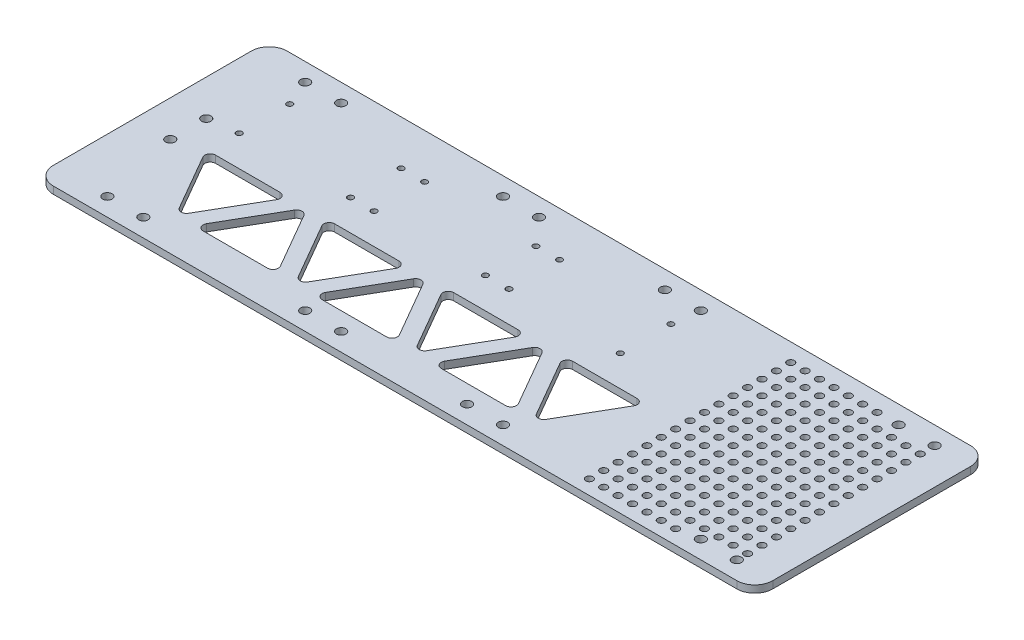
SolidWorks part; units mm, degrees
ref_plane "前视基准面" through (0, 0, 0) normal (0, 0, 1) x (1, 0, 0)
ref_plane "上视基准面" through (0, 0, 0) normal (0, 1, 0) x (1, 0, 0)
ref_plane "右视基准面" through (0, 0, 0) normal (1, 0, 0) x (0, 0, -1)
other "Configuration Table"
sketch "草图1" plane through (0, 0, 0) normal (0, 1, 0) x (1, 0, 0)
  line L1 (0, 0) -> (400, 0)
  line L2 (0, 0) -> (0, -130)
  line L3 (0, -130) -> (400, -130)
  line L4 (400, 0) -> (400, -130)
  dimension "D1" = 130
  dimension "D2" = 400
extrude "凸台-拉伸1" add sketch "草图1" along normal blind 4
sketch "草图2" plane through (0, 4, 0) normal (0, 1, 0) x (1, 0, 0)
  line L0 (45, -59.5) -> (64, -59.5) construction
  line L1 (41, -59.5) -> (45, -59.5)
  line L2 (41, -59.5) -> (41, -75.5)
  line L3 (41, -75.5) -> (45, -75.5)
  line L4 (45, -59.5) -> (45, -75.5)
  line L5 (64, -59.5) -> (68, -59.5)
  line L6 (64, -59.5) -> (64, -75.5)
  line L7 (64, -75.5) -> (68, -75.5)
  line L8 (68, -59.5) -> (68, -75.5)
  line L9 (36.21, -24.8) -> (98.11, -24.8) construction
  line L10 (36.21, -24.8) -> (36.21, -52.9) construction
  line L11 (36.21, -52.9) -> (98.11, -52.9) construction
  line L12 (98.11, -24.8) -> (98.11, -52.9) construction
  line L13 (54.5, -59.5) -> (54.5, -65.549) construction
  line L14 (0, -65) -> (40, -65) construction
  line L15 (0, 0) -> (0, -130) construction
  line L16 (116, -59.5) -> (120, -59.5)
  line L17 (116, -59.5) -> (116, -75.5)
  line L18 (116, -75.5) -> (120, -75.5)
  line L19 (120, -59.5) -> (120, -75.5)
  line L20 (139, -59.5) -> (143, -59.5)
  line L21 (139, -59.5) -> (139, -75.5)
  line L22 (139, -75.5) -> (143, -75.5)
  line L23 (143, -59.5) -> (143, -75.5)
  line L24 (120, -59.5) -> (139, -59.5) construction
  line L25 (111.21, -24.8) -> (173.11, -24.8) construction
  line L26 (111.21, -24.8) -> (111.21, -52.9) construction
  line L27 (111.21, -52.9) -> (173.11, -52.9) construction
  line L28 (173.11, -24.8) -> (173.11, -52.9) construction
  line L29 (129.5, -59.5) -> (129.5, -65.549) construction
  line L30 (191, -59.5) -> (195, -59.5)
  line L31 (191, -59.5) -> (191, -75.5)
  line L32 (191, -75.5) -> (195, -75.5)
  line L33 (195, -59.5) -> (195, -75.5)
  line L34 (214, -59.5) -> (218, -59.5)
  line L35 (214, -59.5) -> (214, -75.5)
  line L36 (214, -75.5) -> (218, -75.5)
  line L37 (218, -59.5) -> (218, -75.5)
  line L38 (195, -59.5) -> (214, -59.5) construction
  line L39 (186.21, -24.8) -> (248.11, -24.8) construction
  line L40 (186.21, -24.8) -> (186.21, -52.9) construction
  line L41 (186.21, -52.9) -> (248.11, -52.9) construction
  line L42 (248.11, -24.8) -> (248.11, -52.9) construction
  line L43 (204.5, -59.5) -> (204.5, -65.549) construction
  circle A0 centre (36.21, -52.9) radius 1.6
  circle A1 centre (36.21, -24.8) radius 1.6
  circle A2 centre (98.11, -52.9) radius 1.6
  circle A3 centre (98.11, -24.8) radius 1.6
  circle A4 centre (40, -65) radius 1 construction
  circle A5 centre (111.21, -52.9) radius 1.6
  circle A6 centre (111.21, -24.8) radius 1.6
  circle A7 centre (173.11, -52.9) radius 1.6
  circle A8 centre (173.11, -24.8) radius 1.6
  circle A9 centre (115, -65) radius 1 construction
  circle A10 centre (186.21, -52.9) radius 1.6
  circle A11 centre (186.21, -24.8) radius 1.6
  circle A12 centre (248.11, -52.9) radius 1.6
  circle A13 centre (248.11, -24.8) radius 1.6
  circle A14 centre (190, -65) radius 1 construction
  dimension "D9" = 2
  dimension "D13" = 3.2
  dimension "D1" = 4
  dimension "D2" = 4
  dimension "D3" = 19
  dimension "D4" = 16
  dimension "D5" = 28.1
  dimension "D6" = 61.9
  dimension "D7" = 12.1
  dimension "D8" = 3.79
  dimension "D10" = 14.5
  dimension "D11" = 5.5
  dimension "D12" = 40
  dimension "D14" = 3
extrude "切除-拉伸1" cut sketch "草图2" against normal blind 4 contours A1 | A0 | A3 | A2 | A5 | A7 | A8 | A11 | A10 | A13 | A12 | A6
sketch "草图3" plane through (0, 4, 0) normal (0, 1, 0) x (1, 0, 0)
  line L0 (0, -65) -> (25.2073, -65) construction
  line L1 (0, 0) -> (0, -130) construction
  line L2 (20, -75) -> (20, -55) construction
  circle A0 centre (20, -75) radius 2.6
  circle A1 centre (20, -55) radius 2.6
  dimension "D1" = 5.2
  dimension "D2" = 20
  dimension "D3" = 20
extrude "切除-拉伸2" cut sketch "草图3" against normal through all
sketch "草图4" plane through (0, 4, 0) normal (0, 1, 0) x (1, 0, 0)
  line L0 (67.16, -24.8) -> (67.16, 18.7842) construction
  line L1 (0, -130) -> (300, -130)
  line L2 (0, -130) -> (0, -180)
  line L3 (0, -180) -> (300, -180)
  line L4 (300, -130) -> (300, -180)
  line L5 (36.21, -24.8) -> (98.11, -24.8) construction
  line L6 (142.16, -24.8) -> (142.16, 18.7842) construction
  line L7 (111.21, -24.8) -> (173.11, -24.8) construction
  line L8 (217.16, -24.8) -> (217.16, 18.7842) construction
  line L9 (186.21, -24.8) -> (248.11, -24.8) construction
  line L10 (42.16, 30) -> (42.16, 0)
  line L11 (42.16, 30) -> (92.16, 30)
  line L12 (42.16, 0) -> (92.16, 0)
  line L13 (92.16, 30) -> (92.16, 0)
  line L14 (42.16, 30) -> (92.16, 0) construction
  line L15 (42.16, 0) -> (92.16, 30) construction
  line L16 (117.16, 30) -> (117.16, 0)
  line L17 (117.16, 30) -> (167.16, 30)
  line L18 (167.16, 30) -> (167.16, 0)
  line L19 (117.16, 0) -> (167.16, 0)
  line L20 (192.16, 30) -> (192.16, 0)
  line L21 (192.16, 30) -> (242.16, 30)
  line L22 (242.16, 30) -> (242.16, 0)
  line L23 (192.16, 0) -> (242.16, 0)
  point P18 (67.16, 15)
  dimension "D1" = 300
  dimension "D2" = 50
  dimension "D3" = 50
  dimension "D4" = 30
  dimension "D5" = 3
extrude "凸台-拉伸2" [suppressed] add sketch "草图4" against normal up to surface (4 mm away)
sketch "草图5" plane through (0, 4, 0) normal (0, 1, 0) x (1, 0, 0)
  line L0 (140, -10) -> (160, -10) construction
  line L1 (30, -10) -> (50, -10) construction
  line L2 (0, 0) -> (0, -130) construction
  line L3 (0, -65) -> (40, -65) construction
  line L4 (0, -65) -> (40, -65) construction
  line L5 (230, -10) -> (250, -10) construction
  line L6 (360, -10) -> (380, -10) construction
  line L7 (360, -120) -> (380, -120) construction
  line L8 (230, -120) -> (250, -120) construction
  line L9 (30, -120) -> (50, -120) construction
  line L10 (140, -120) -> (160, -120) construction
  circle A0 centre (30, -10) radius 2.6
  circle A1 centre (50, -10) radius 2.6
  circle A4 centre (140, -10) radius 2.6
  circle A5 centre (160, -10) radius 2.6
  circle A8 centre (230, -10) radius 2.6
  circle A9 centre (250, -10) radius 2.6
  circle A12 centre (360, -10) radius 2.6
  circle A13 centre (380, -10) radius 2.6
  circle A16 centre (380, -120) radius 2.6
  circle A17 centre (360, -120) radius 2.6
  circle A18 centre (250, -120) radius 2.6
  circle A19 centre (230, -120) radius 2.6
  circle A20 centre (160, -120) radius 2.6
  circle A21 centre (140, -120) radius 2.6
  circle A22 centre (50, -120) radius 2.6
  circle A23 centre (30, -120) radius 2.6
  dimension "D1" = 5.2
  dimension "D6" = 110
  dimension "D7" = 130
  dimension "D5" = 90
  dimension "D2" = 55
  dimension "D3" = 20
  dimension "D4" = 30
extrude "切除-拉伸3" cut sketch "草图5" against normal through all
sketch "草图6" plane through (0, 4, 0) normal (0, 1, 0) x (1, 0, 0)
  line L8 (390, -112) -> (346, -112)
  line L9 (346, -112) -> (346, -101)
  line L12 (346, -101) -> (332, -101)
  line L13 (332, -101) -> (332, -79)
  line L16 (332, -79) -> (346, -79)
  line L17 (346, -79) -> (346, -68)
  line L18 (346, -68) -> (390, -68)
  line L19 (390, -68) -> (390, -112)
  line L20 (0, -130) -> (400, -130) construction
  line L21 (400, -130) -> (400, 0) construction
  circle A6 centre (335.5, -114.5) radius 2.1
  circle A7 centre (335.5, -65.5) radius 2.1
  dimension "D3" = 22
  dimension "D11" = 4.2
  dimension "D1" = 44
  dimension "D2" = 44
  dimension "D4" = 11
  dimension "D5" = 14
  dimension "D6" = 14
  dimension "D7" = 13.5
  dimension "D8" = 13.5
  dimension "D9" = 54.5
  dimension "D10" = 54.5
  dimension "D12" = 18
  dimension "D13" = 10
extrude "切除-拉伸4" [suppressed] cut sketch "草图6" against normal through all
sketch "草图7" plane through (0, 4, 0) normal (0, 1, 0) x (1, 0, 0)
  line L0 (380, -66) -> (380, -110)
  line L1 (336, -66) -> (347, -66)
  line L2 (336, -66) -> (336, -110)
  line L3 (336, -110) -> (380, -110)
  line L4 (369, -52) -> (347, -52)
  line L5 (347, -52) -> (347, -66)
  line L6 (369, -66) -> (380, -66)
  line L7 (369, -52) -> (369, -66)
  line L8 (333.5, -55.5) -> (382.5, -55.5) construction
  line L9 (400, -130) -> (400, 0) construction
  line L12 (358, -110) -> (358, -52) construction
  line L13 (0, -130) -> (400, -130) construction
  circle A0 centre (333.5, -55.5) radius 2.1
  circle A1 centre (382.5, -55.5) radius 2.1
  point P10 (358, -52)
  point P13 (380, -88)
  dimension "D3" = 4.2
  dimension "D11" = 20
  dimension "D1" = 44
  dimension "D2" = 14
  dimension "D4" = 22
  dimension "D5" = 11
  dimension "D6" = 44
  dimension "D7" = 13.5
  dimension "D8" = 13.5
  dimension "D9" = 11
  dimension "D10" = 44
  dimension "D12" = 20
  dimension "D13" = 54.5
extrude "切除-拉伸5" [suppressed] cut sketch "草图7" against normal through all
sketch "草图8" plane through (0, 4, 0) normal (0, 1, 0) x (1, 0, 0)
  line L0 (400, 0) -> (0, 0) construction
  line L1 (0, 0) -> (0, -130) construction
  circle A0 centre (300, -10) radius 2
  circle A1 centre (308, -10) radius 2
  circle A2 centre (316, -10) radius 2
  circle A3 centre (324, -10) radius 2
  circle A4 centre (332, -10) radius 2
  circle A5 centre (340, -10) radius 2
  circle A6 centre (348, -10) radius 2
  circle A11 centre (308, -18) radius 2
  circle A12 centre (316, -18) radius 2
  circle A13 centre (324, -18) radius 2
  circle A14 centre (332, -18) radius 2
  circle A15 centre (340, -18) radius 2
  circle A16 centre (348, -18) radius 2
  circle A17 centre (356, -18) radius 2
  circle A18 centre (364, -18) radius 2
  circle A19 centre (372, -18) radius 2
  circle A20 centre (380, -18) radius 2
  circle A21 centre (308, -26) radius 2
  circle A22 centre (316, -26) radius 2
  circle A23 centre (324, -26) radius 2
  circle A24 centre (332, -26) radius 2
  circle A25 centre (340, -26) radius 2
  circle A26 centre (348, -26) radius 2
  circle A27 centre (356, -26) radius 2
  circle A28 centre (364, -26) radius 2
  circle A29 centre (372, -26) radius 2
  circle A30 centre (380, -26) radius 2
  circle A31 centre (308, -34) radius 2
  circle A32 centre (316, -34) radius 2
  circle A33 centre (324, -34) radius 2
  circle A34 centre (332, -34) radius 2
  circle A35 centre (340, -34) radius 2
  circle A36 centre (348, -34) radius 2
  circle A37 centre (356, -34) radius 2
  circle A38 centre (364, -34) radius 2
  circle A39 centre (372, -34) radius 2
  circle A40 centre (380, -34) radius 2
  circle A41 centre (308, -42) radius 2
  circle A42 centre (316, -42) radius 2
  circle A43 centre (324, -42) radius 2
  circle A44 centre (332, -42) radius 2
  circle A45 centre (340, -42) radius 2
  circle A46 centre (348, -42) radius 2
  circle A47 centre (356, -42) radius 2
  circle A48 centre (364, -42) radius 2
  circle A49 centre (372, -42) radius 2
  circle A50 centre (380, -42) radius 2
  circle A51 centre (308, -50) radius 2
  circle A52 centre (316, -50) radius 2
  circle A53 centre (324, -50) radius 2
  circle A54 centre (332, -50) radius 2
  circle A55 centre (340, -50) radius 2
  circle A56 centre (348, -50) radius 2
  circle A57 centre (356, -50) radius 2
  circle A58 centre (364, -50) radius 2
  circle A59 centre (372, -50) radius 2
  circle A60 centre (380, -50) radius 2
  circle A61 centre (308, -58) radius 2
  circle A62 centre (316, -58) radius 2
  circle A63 centre (324, -58) radius 2
  circle A64 centre (332, -58) radius 2
  circle A65 centre (340, -58) radius 2
  circle A66 centre (348, -58) radius 2
  circle A67 centre (356, -58) radius 2
  circle A68 centre (364, -58) radius 2
  circle A69 centre (372, -58) radius 2
  circle A70 centre (380, -58) radius 2
  circle A71 centre (308, -66) radius 2
  circle A72 centre (316, -66) radius 2
  circle A73 centre (324, -66) radius 2
  circle A74 centre (332, -66) radius 2
  circle A75 centre (340, -66) radius 2
  circle A76 centre (348, -66) radius 2
  circle A77 centre (356, -66) radius 2
  circle A78 centre (364, -66) radius 2
  circle A79 centre (372, -66) radius 2
  circle A80 centre (380, -66) radius 2
  circle A81 centre (308, -74) radius 2
  circle A82 centre (316, -74) radius 2
  circle A83 centre (324, -74) radius 2
  circle A84 centre (332, -74) radius 2
  circle A85 centre (340, -74) radius 2
  circle A86 centre (348, -74) radius 2
  circle A87 centre (356, -74) radius 2
  circle A88 centre (364, -74) radius 2
  circle A89 centre (372, -74) radius 2
  circle A90 centre (380, -74) radius 2
  circle A91 centre (308, -82) radius 2
  circle A92 centre (316, -82) radius 2
  circle A93 centre (324, -82) radius 2
  circle A94 centre (332, -82) radius 2
  circle A95 centre (340, -82) radius 2
  circle A96 centre (348, -82) radius 2
  circle A97 centre (356, -82) radius 2
  circle A98 centre (364, -82) radius 2
  circle A99 centre (372, -82) radius 2
  circle A100 centre (380, -82) radius 2
  circle A101 centre (308, -90) radius 2
  circle A102 centre (316, -90) radius 2
  circle A103 centre (324, -90) radius 2
  circle A104 centre (332, -90) radius 2
  circle A105 centre (340, -90) radius 2
  circle A106 centre (348, -90) radius 2
  circle A107 centre (356, -90) radius 2
  circle A108 centre (364, -90) radius 2
  circle A109 centre (372, -90) radius 2
  circle A110 centre (380, -90) radius 2
  circle A111 centre (308, -98) radius 2
  circle A112 centre (316, -98) radius 2
  circle A113 centre (324, -98) radius 2
  circle A114 centre (332, -98) radius 2
  circle A115 centre (340, -98) radius 2
  circle A116 centre (348, -98) radius 2
  circle A117 centre (356, -98) radius 2
  circle A118 centre (364, -98) radius 2
  circle A119 centre (372, -98) radius 2
  circle A120 centre (380, -98) radius 2
  circle A121 centre (300, -18) radius 2
  circle A122 centre (300, -26) radius 2
  circle A123 centre (300, -34) radius 2
  circle A124 centre (300, -42) radius 2
  circle A125 centre (300, -50) radius 2
  circle A126 centre (300, -58) radius 2
  circle A127 centre (300, -66) radius 2
  circle A128 centre (300, -74) radius 2
  circle A129 centre (300, -82) radius 2
  circle A130 centre (300, -90) radius 2
  circle A131 centre (300, -98) radius 2
  circle A132 centre (300, -106) radius 2
  circle A133 centre (308, -106) radius 2
  circle A134 centre (316, -106) radius 2
  circle A135 centre (324, -106) radius 2
  circle A136 centre (332, -106) radius 2
  circle A137 centre (340, -106) radius 2
  circle A138 centre (348, -106) radius 2
  circle A139 centre (356, -106) radius 2
  circle A140 centre (364, -106) radius 2
  circle A141 centre (372, -106) radius 2
  circle A142 centre (380, -106) radius 2
  circle A143 centre (300, -114) radius 2
  circle A144 centre (308, -114) radius 2
  circle A145 centre (316, -114) radius 2
  circle A146 centre (324, -114) radius 2
  circle A147 centre (332, -114) radius 2
  circle A148 centre (340, -114) radius 2
  circle A149 centre (348, -114) radius 2
  circle A150 centre (356, -114) radius 2
  circle A151 centre (364, -114) radius 2
  circle A152 centre (372, -114) radius 2
  circle A153 centre (380, -114) radius 2
  circle A154 centre (300, -122) radius 2
  circle A155 centre (308, -122) radius 2
  circle A156 centre (316, -122) radius 2
  circle A157 centre (324, -122) radius 2
  circle A158 centre (332, -122) radius 2
  circle A159 centre (340, -122) radius 2
  circle A160 centre (348, -122) radius 2
  circle A165 centre (356, -10) radius 2 [skipped]
  circle A166 centre (364, -10) radius 2 [skipped]
  circle A167 centre (372, -10) radius 2 [skipped]
  circle A168 centre (380, -10) radius 2 [skipped]
  circle A169 centre (356, -122) radius 2 [skipped]
  circle A170 centre (364, -122) radius 2 [skipped]
  circle A171 centre (372, -122) radius 2 [skipped]
  circle A172 centre (380, -122) radius 2 [skipped]
  dimension "D1" = 4
  dimension "D3" = 300
  dimension "D2" = 10
  dimension "D4" = 11
  dimension "D5" = 15
extrude "切除-拉伸6" cut sketch "草图8" against normal through all
sketch "草图9" plane through (0, 4, 0) normal (0, 1, 0) x (1, 0, 0)
  line L0 (0, -130) -> (400, -130) construction
  line L1 (185.4166, -77) -> (234.4166, -77) construction
  line L2 (185.4166, -77) -> (185.4166, -126) construction
  line L3 (185.4166, -126) -> (234.4166, -126) construction
  line L4 (234.4166, -77) -> (234.4166, -126) construction
  circle A0 centre (185.4166, -77) radius 1.6
  circle A1 centre (185.4166, -126) radius 1.6
  circle A2 centre (234.4166, -126) radius 1.6
  circle A3 centre (234.4166, -77) radius 1.6
  dimension "D3" = 3.2
  dimension "D1" = 49
  dimension "D2" = 49
  dimension "D4" = 4
extrude "切除-拉伸7" [suppressed] cut sketch "草图9" against normal through all
fillet "圆角1" radius 10 4 edges at (400, 2, 130) (400, 2, 0) (0, 2, 0) (0, 2, 130)
sketch "草图10" plane through (0, 4, 0) normal (0, 1, 0) x (1, 0, 0)
  line L0 (0, -10) -> (0, -120) construction
  line L1 (81.19, -70) -> (35, -70)
  line L2 (35, -70) -> (58.095, -110.0017)
  line L3 (58.095, -110.0017) -> (81.19, -70)
  line L4 (114.285, -110.0017) -> (91.19, -70)
  line L5 (91.19, -70) -> (68.095, -110.0017)
  line L6 (68.095, -110.0017) -> (114.285, -110.0017)
  line L7 (10, -130) -> (390, -130) construction
  line L8 (147.38, -70) -> (101.19, -70)
  line L9 (101.19, -70) -> (124.285, -110.0017)
  line L10 (124.285, -110.0017) -> (147.38, -70)
  line L11 (180.475, -110.0017) -> (157.38, -70)
  line L12 (157.38, -70) -> (134.285, -110.0017)
  line L13 (134.285, -110.0017) -> (180.475, -110.0017)
  line L14 (213.57, -70) -> (167.38, -70)
  line L15 (167.38, -70) -> (190.475, -110.0017)
  line L16 (190.475, -110.0017) -> (213.57, -70)
  line L17 (246.665, -110.0017) -> (223.57, -70)
  line L18 (223.57, -70) -> (200.475, -110.0017)
  line L19 (200.475, -110.0017) -> (246.665, -110.0017)
  line L20 (279.76, -70) -> (233.57, -70)
  line L21 (233.57, -70) -> (256.665, -110.0017)
  line L22 (256.665, -110.0017) -> (279.76, -70)
  line L26 (312.855, -110.0017) -> (289.76, -70) [skipped]
  line L27 (289.76, -70) -> (266.665, -110.0017) [skipped]
  line L28 (266.665, -110.0017) -> (312.855, -110.0017) [skipped]
  circle A0 centre (58.095, -83.3339) radius 13.3339 construction
  circle A1 centre (91.19, -96.6678) radius 13.3339 construction
  dimension "D1" = 35
  dimension "D2" = 60
  dimension "D3" = 46.19
  dimension "D4" = 10
  dimension "D5" = 4
extrude "切除-拉伸8" cut sketch "草图10" against normal through all
fillet "圆角2" radius 3 21 edges at (233.57, 2, 70) (279.76, 2, 70) (256.665, 2, 110.0017) (246.665, 2, 110.0017) (200.475, 2, 110.0017) (223.57, 2, 70) (213.57, 2, 70) (190.475, 2, 110.0017) (167.38, 2, 70) (180.475, 2, 110.0017) (157.38, 2, 70) (134.285, 2, 110.0017) (147.38, 2, 70) (101.19, 2, 70) (124.285, 2, 110.0017) (114.285, 2, 110.0017) (91.19, 2, 70) (68.095, 2, 110.0017) (58.095, 2, 110.0017) (81.19, 2, 70) (35, 2, 70)
